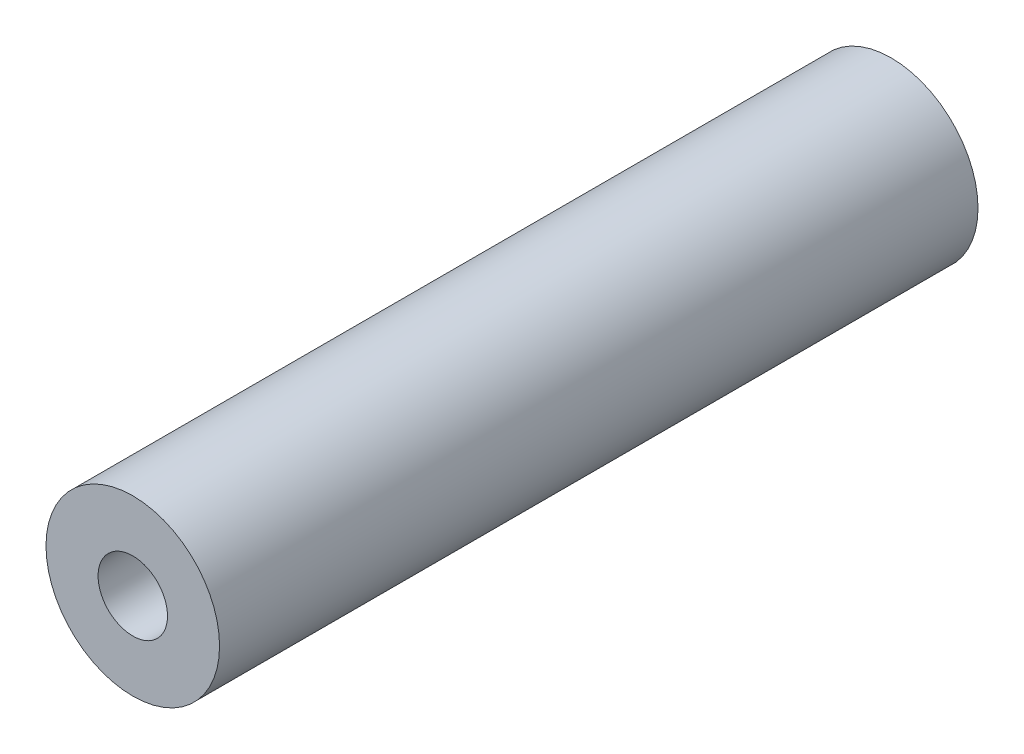
SolidWorks part; units mm, degrees
ref_plane "前视基准面" through (0, 0, 0) normal (0, 0, 1) x (1, 0, 0)
ref_plane "上视基准面" through (0, 0, 0) normal (0, 1, 0) x (1, 0, 0)
ref_plane "右视基准面" through (0, 0, 0) normal (1, 0, 0) x (0, 0, -1)
sketch "草图1" plane through (0, 0, 0) normal (0, 0, 1) x (1, 0, 0)
  circle A0 centre (0, 0) radius 5
  circle A1 centre (0, 0) radius 2
extrude "凸台-拉伸1" add sketch "草图1" along normal blind 43.7
